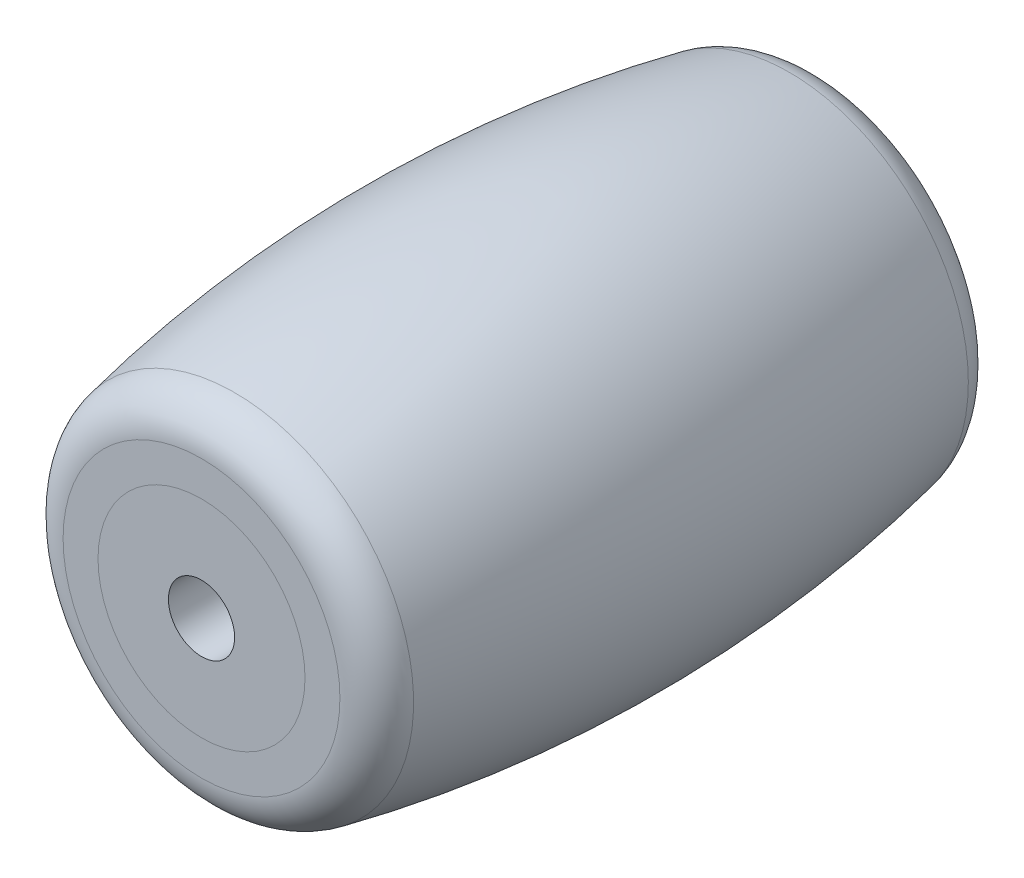
SolidWorks part; units mm, degrees
ref_plane "Ebene vorne" through (0, 0, 0) normal (0, 0, 1) x (1, 0, 0)
ref_plane "Ebene oben" through (0, 0, 0) normal (0, 1, 0) x (1, 0, 0)
ref_plane "Ebene rechts" through (0, 0, 0) normal (1, 0, 0) x (0, 0, -1)
sketch "Skizze1" plane through (0, 0, 0) normal (1, 0, 0) x (0, 0, -1)
  line L0 (-18.5513, 0) -> (18.5513, 0) construction
  line L1 (-15, 5) -> (15, 5)
  line L2 (-15, 5) -> (-15, 8.2993)
  line L4 (15, 5) -> (15, 8.2993)
  line L5 (0, -57) -> (0, 24.0864) construction
  arc A1 (15, 8.2993) -> (-15, 8.2993) centre (0, -57) ccw
  point P6 (0, 5)
  dimension "D1" = 30
  dimension "D4" = 67
  dimension "D3" = 20
  dimension "D2" = 5
revolve "Rotation1" add sketch "Skizze1" angle 360 about L0
fillet "Verrundung1" radius 2 2 edges at (8.2993, 0, -15) (8.2993, 0, 15)
sketch "Skizze2" plane through (0, 0, 0) normal (0, 0, 1) x (1, 0, 0)
  circle A0 centre (0, 0) radius 5
  circle A1 centre (0, 0) radius 1.6
  dimension "D1" = 10
  dimension "D2" = 3.2
extrude "Aufsatz-Linear austragen1" add sketch "Skizze2" along normal through all and the other way through all separate body
